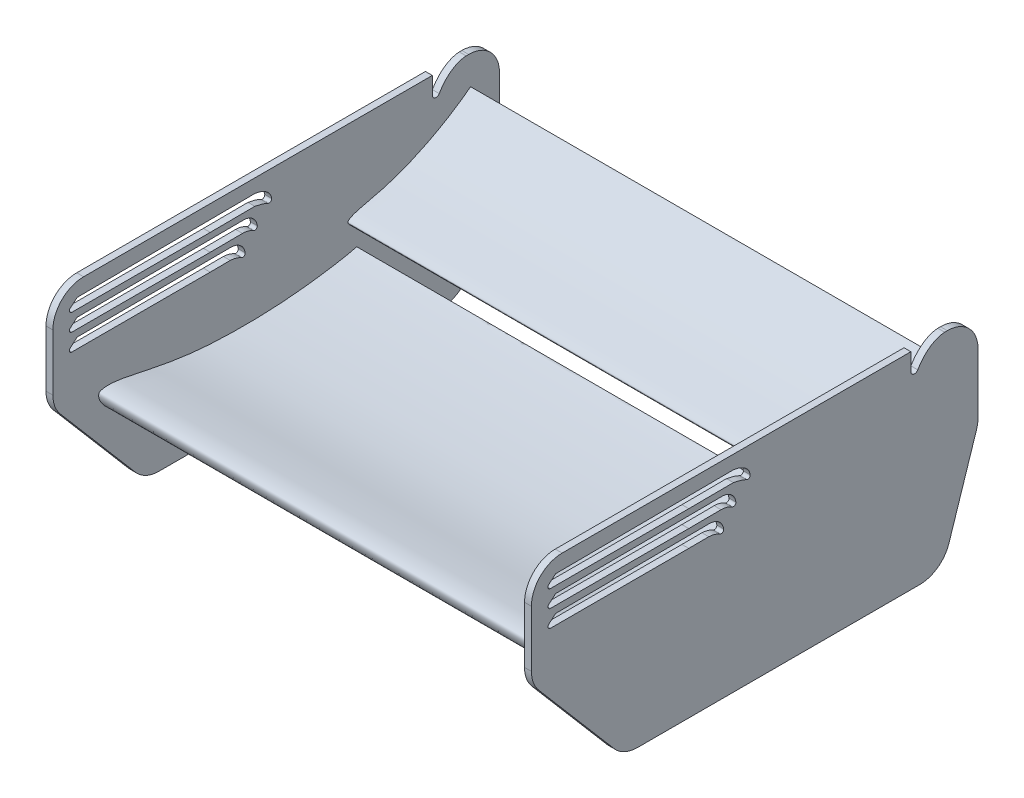
SolidWorks part; units mm, degrees
ref_plane "Front Plane" through (0, 0, 0) normal (0, 0, 1) x (1, 0, 0)
ref_plane "Top Plane" through (0, 0, 0) normal (0, 1, 0) x (1, 0, 0)
ref_plane "Right Plane" through (0, 0, 0) normal (1, 0, 0) x (0, 0, -1)
ref_plane "Soft Top Limit" through (0, 1174.6, 0) normal (0, 1, 0) x (1, 0, 0)
ref_plane "Soft Rear Limit" through (0, 0, -1192.975) normal (0, 0, 1) x (1, 0, 0)
ref_plane "Soft Right Limit" through (-501.65, 0, 0) normal (1, 0, 0) x (0, 0, -1)
ref_plane "Soft Left Limit" through (501.65, 0, 0) normal (1, 0, 0) x (0, 0, -1)
ref_plane "Soft Front Limit" through (0, 0, -165.1) normal (0, 0, 1) x (1, 0, 0)
ref_plane "Slant Limit" through (0, 528.6251, -619.2711) normal (0, -0.6492, 0.7606) x (1, 0, 0)
ref_plane "Bottom" through (0, 476.25, 0) normal (0, 1, 0) x (1, 0, 0)
ref_plane "Midplane" through (0, 0, 0) normal (1, 0, 0) x (0, 0, -1)
curve "Imported Airfoil Curve"
  spline degree 3 poles (0, 2520.0207, 6.126) (0, 2544.889, -1.81) (0, 2521.8965, 7.8839) (0, 2505.3253, 17.7145) (0, 2467.7144, 38.5723) (0, 2424.2142, 62.3813) (0, 2368.0949, 87.8078) (0, 2301.3729, 113.3478) (0, 2223.8362, 140.5377) (0, 2136.6129, 169.2441) (0, 2040.932, 199.097) (0, 1938.2341, 229.6055) (0, 1829.9414, 260.0781) (0, 1717.5266, 289.8586) (0, 1602.4273, 318.1375) (0, 1486.0259, 343.9752) (0, 1369.6902, 366.5754) (0, 1254.3666, 384.7865) (0, 1140.5393, 397.0034) (0, 1028.6357, 403.0127) (0, 919.0585, 402.9406) (0, 812.3986, 397.0375) (0, 709.2785, 385.5985) (0, 610.4299, 369.039) (0, 516.5862, 348.1086) (0, 428.5874, 323.3415) (0, 347.2653, 295.2055) (0, 273.332, 264.2656) (0, 207.4209, 231.0894) (0, 150.0337, 196.3024) (0, 101.596, 160.572) (0, 62.3674, 124.65) (0, 32.4977, 89.3959) (0, 12.0597, 55.6746) (0, 1.683, 26.6201) (0, -0.5567, 6.5526) (0, 0.5894, -3.9947) (0, 1.6947, -9.1451) (0, 2.8711, -12.4915) (0, 3.9449, -14.9776) (0, 4.8993, -16.669) (0, 5.9763, -18.2433) (0, 7.3264, -19.6365) (0, 8.8595, -20.9434) (0, 11.1868, -22.7306) (0, 14.6073, -24.7406) (0, 20.085, -27.4067) (0, 26.8353, -29.9257) (0, 44.6446, -35.1819) (0, 77.8093, -38.8998) (0, 130.2841, -38.2927) (0, 196.3018, -31.4611) (0, 276.2192, -18.4434) (0, 370.8288, 0.8611) (0, 480.7331, 24.811) (0, 605.9792, 50.0099) (0, 745.0759, 74.1542) (0, 895.4497, 95.0846) (0, 1053.6786, 110.004) (0, 1215.6439, 118.3392) (0, 1377.6893, 121.6348) (0, 1537.1174, 120.5125) (0, 1691.5141, 115.2051) (0, 1838.3121, 105.7388) (0, 1975.028, 93.0069) (0, 2099.5942, 78.4581) (0, 2210.5746, 63.1262) (0, 2306.3634, 48.0168) (0, 2387.2069, 33.7158) (0, 2449.0745, 22.0129) (0, 2499.1865, 10.4993) (0, 2520.0207, 6.126) (0, 2544.889, -1.81) (0, 2521.8965, 7.8839) knots -0.016237 -0.007308 -0.001841 0 0.001813 0.006911 0.014576 0.024172 0.035572 0.049013 0.064513 0.081849 0.100772 0.120997 0.142228 0.164173 0.186537 0.209023 0.231367 0.25332 0.274804 0.295858 0.316449 0.336531 0.356033 0.374893 0.39299 0.410197 0.426388 0.441459 0.455334 0.467938 0.479236 0.489204 0.497851 0.505194 0.511308 0.515097 0.516441 0.517273 0.51806 0.518436 0.518797 0.519154 0.519508 0.519887 0.520289 0.52116 0.522116 0.52372 0.525214 0.532575 0.542381 0.554776 0.569931 0.588005 0.609188 0.633329 0.660001 0.688743 0.718873 0.749543 0.780127 0.810209 0.839387 0.867183 0.893104 0.91676 0.937874 0.956199 0.971544 0.983763 0.992692 0.998159 1 1.001813 1.006911 1.014576 periodic
sketch "Airfoils Sketch" plane through (0, 0, 0) normal (1, 0, 0) x (0, 0, -1)
  line L0 (165.1, 1174.6) -> (165.1, 1060.6753) construction
  line L1 (165.1, 1060.6753) -> (663.9798, 476.25) construction
  line L2 (663.9798, 476.25) -> (1192.975, 476.25) construction
  line L3 (1192.975, 476.25) -> (1192.975, 1174.6) construction
  line L4 (1192.975, 1174.6) -> (165.1, 1174.6) construction
  line L5 (509.9361, 1174.6) -> (-509.9361, 1174.6) construction
  line L6 (165.1, 67.0076) -> (165.1, -67.0076) construction
  line L7 (364.7288, 826.8151) -> (873.8134, 230.4351) construction
  line L8 (279.3831, 476.25) -> (-279.3831, 476.25) construction
  line L9 (1192.975, 353.2696) -> (1192.975, -353.2696) construction
  line L10 (364.5896, 868.5327) -> (364.5896, 946) construction
  line L11 (897.9896, 878.5574) -> (897.9896, 1013.4426) construction
  line L12 (897.9896, 946) -> (364.5896, 946) construction
  line L13 (262.9896, 946) -> (1192.975, 946) construction
  line L14 (855.8887, 1048.5614) -> (904.1623, 945.0386) construction
  line L15 (1108.8736, 1167.1505) -> (1157.6222, 1062.6086) construction
  line L16 (1133.2479, 1114.8795) -> (880.0255, 996.8) construction
  line L30 (856.3371, 1047.6) -> (1192.975, 1047.6) construction
  spline S0 degree 3 poles (893.7912, 944.7229) (899.0172, 946.3778) (894.1843, 944.3529) (890.6998, 942.2962) (882.7919, 937.9336) (873.6459, 932.9541) (861.8492, 927.6408) (847.826, 922.3086) (831.5308, 916.6349) (813.2009, 910.6474) (793.0943, 904.4229) (771.5139, 898.0641) (748.7586, 891.7155) (725.138, 885.5141) (700.9544, 879.6292) (676.4985, 874.2577) (652.0578, 869.5659) (627.8318, 865.7954) (603.9228, 863.283) (580.4206, 862.0732) (557.4098, 862.1394) (535.0144, 863.4287) (513.3649, 865.8789) (492.6147, 869.4025) (472.9176, 873.8415) (454.4497, 879.0835) (437.3855, 885.0299) (421.8742, 891.5616) (408.0485, 898.5592) (396.0136, 905.8911) (385.8586, 913.417) (377.6374, 920.9787) (371.3813, 928.3959) (367.1052, 935.4868) (364.9396, 941.5929) (364.4786, 945.8081) (364.7242, 948.0225) (364.9587, 949.1035) (365.2073, 949.8057) (365.434, 950.3273) (365.6352, 950.682) (365.8621, 951.0121) (366.1463, 951.304) (366.4688, 951.5778) (366.9584, 951.952) (367.6776, 952.3725) (368.8291, 952.9298) (370.2479, 953.4556) (373.9902, 954.5511) (380.9564, 955.3164) (391.9757, 955.1645) (405.8359, 953.6991) (422.6123, 950.9282) (442.4709, 946.8302) (465.5393, 941.7496) (491.8288, 936.3995) (521.0273, 931.2645) (552.5956, 926.7991) (585.8161, 923.5923) (619.8244, 921.7664) (653.8518, 920.9989) (687.3317, 921.1602) (719.7569, 922.2028) (750.5884, 924.1223) (779.3042, 926.7322) (805.4694, 929.7293) (828.782, 932.8973) (848.9044, 936.0255) (865.8879, 938.991) (878.8853, 941.4197) (889.4141, 943.8142) (893.7912, 944.7229) (899.0172, 946.3778) (894.1843, 944.3529) knots -0.016237 -0.007308 -0.001841 0 0.001813 0.006911 0.014576 0.024172 0.035572 0.049013 0.064513 0.081849 0.100772 0.120997 0.142228 0.164173 0.186537 0.209023 0.231367 0.25332 0.274804 0.295858 0.316449 0.336531 0.356033 0.374893 0.39299 0.410197 0.426388 0.441459 0.455334 0.467938 0.479236 0.489204 0.497851 0.505194 0.511308 0.515097 0.516441 0.517273 0.51806 0.518436 0.518797 0.519154 0.519508 0.519887 0.520289 0.52116 0.522116 0.52372 0.525214 0.532575 0.542381 0.554776 0.569931 0.588005 0.609188 0.633329 0.660001 0.688743 0.718873 0.749543 0.780127 0.810209 0.839387 0.867183 0.893104 0.91676 0.937874 0.956199 0.971544 0.983763 0.992692 0.998159 1 1.001813 1.006911 1.014576 only from (897.9896, 946) to (897.9896, 946)
  spline S1 degree 3 poles (1131.5375, 1113.3438) (1133.6521, 1115.2864) (1131.806, 1113.2552) (1130.6071, 1111.5075) (1127.8187, 1107.6858) (1124.5791, 1103.2972) (1120.1551, 1098.1634) (1114.6782, 1092.5276) (1108.1983, 1086.2269) (1100.822, 1079.3267) (1092.6546, 1071.9207) (1083.8174, 1064.1247) (1074.4201, 1056.0734) (1064.5795, 1047.9005) (1054.4014, 1039.7532) (1043.9805, 1031.7893) (1033.4164, 1024.1515) (1022.7502, 1016.9986) (1011.956, 1010.5131) (1001.0665, 1004.736) (990.1279, 999.6735) (979.2106, 995.3279) (968.3905, 991.6985) (957.7597, 988.7777) (947.4262, 986.5247) (937.4984, 984.925) (928.0811, 983.9704) (919.2715, 983.6375) (911.1589, 983.8989) (903.8225, 984.7154) (897.3355, 986.0401) (891.7587, 987.81) (887.1468, 989.9462) (883.547, 992.3659) (881.1672, 994.7853) (880.0153, 996.6843) (879.6417, 997.7899) (879.5137, 998.355) (879.4763, 998.7434) (879.4684, 999.0412) (879.4854, 999.2542) (879.52, 999.4611) (879.5903, 999.6626) (879.6829, 999.864) (879.8324, 1000.15) (880.0808, 1000.5088) (880.5041, 1001.0283) (881.0612, 1001.592) (882.5953, 1002.9405) (885.733, 1004.8459) (890.9978, 1007.2132) (897.9021, 1009.5858) (906.4798, 1011.9841) (916.8145, 1014.4348) (928.8905, 1017.1296) (942.5554, 1020.4095) (957.5536, 1024.4354) (973.5286, 1029.3038) (990.0094, 1035.1356) (1006.5584, 1041.7972) (1022.8822, 1048.9655) (1038.7405, 1056.4536) (1053.903, 1064.1266) (1068.1148, 1071.863) (1081.1694, 1079.4589) (1092.9274, 1086.674) (1103.2934, 1093.3387) (1112.1536, 1099.2783) (1119.5597, 1104.4457) (1125.1924, 1108.476) (1129.6607, 1111.9435) (1131.5375, 1113.3438) (1133.6521, 1115.2864) (1131.806, 1113.2552) knots -0.016237 -0.007308 -0.001841 0 0.001813 0.006911 0.014576 0.024172 0.035572 0.049013 0.064513 0.081849 0.100772 0.120997 0.142228 0.164173 0.186537 0.209023 0.231367 0.25332 0.274804 0.295858 0.316449 0.336531 0.356033 0.374893 0.39299 0.410197 0.426388 0.441459 0.455334 0.467938 0.479236 0.489204 0.497851 0.505194 0.511308 0.515097 0.516441 0.517273 0.51806 0.518436 0.518797 0.519154 0.519508 0.519887 0.520289 0.52116 0.522116 0.52372 0.525214 0.532575 0.542381 0.554776 0.569931 0.588005 0.609188 0.633329 0.660001 0.688743 0.718873 0.749543 0.780127 0.810209 0.839387 0.867183 0.893104 0.91676 0.937874 0.956199 0.971544 0.983763 0.992692 0.998159 1 1.001813 1.006911 1.014576 only from (1133.2479, 1114.8795) to (1133.2479, 1114.8795)
  dimension "D1" = 533.4
  dimension "D2" = 228.6
  dimension "D3" = 0
  dimension "D5" = 279.4
  dimension "D6" = 59.7205
extrude "Extruded Airfoils" add sketch "Airfoils Sketch" along normal offset from surface (487.45 mm away) 14.2 up to plane "Soft Left Limit"
sketch "Endplate Sketch" plane through (501.65, 0, 0) normal (1, 0, 0) x (0, 0, -1)
  line L6 (333.4477, 1174.6) -> (1129.475, 1174.6)
  line L7 (1192.975, 1174.6) -> (165.1, 1174.6) construction
  line L8 (1192.975, 1111.1) -> (1192.975, 986.6717)
  line L9 (1192.975, 476.25) -> (1192.975, 1174.6) construction
  line L11 (1189.8464, 966.9854) -> (1132.8969, 792.34)
  line L12 (1072.5255, 748.5263) -> (489.1772, 748.5263)
  line L19 (440.8805, 770.7991) -> (285.151, 953.2323)
  line L26 (269.9477, 994.4595) -> (269.9477, 1111.1)
  line L28 (165.1, 1060.6753) -> (663.9798, 476.25) construction
  arc A12 (1129.475, 1174.6) -> (1192.975, 1111.1) centre (1129.475, 1111.1) cw
  arc A13 (1192.975, 986.6717) -> (1189.8464, 966.9854) centre (1129.475, 986.6717) cw
  arc A14 (1132.8969, 792.34) -> (1072.5255, 748.5263) centre (1072.5255, 812.0263) cw
  arc A15 (489.1772, 748.5263) -> (440.8805, 770.7991) centre (489.1772, 812.0263) cw
  arc A16 (285.151, 953.2323) -> (269.9477, 994.4595) centre (333.4477, 994.4595) cw
  arc A17 (333.4477, 1174.6) -> (269.9477, 1111.1) centre (333.4477, 1111.1) ccw
  point P16 (1192.975, 1174.6)
  point P19 (1192.975, 976.5799)
  point P29 (269.9477, 1174.6)
  dimension "D1" = 63.5
extrude "Extruded Endplate" add sketch "Endplate Sketch" against normal up to surface (14.2 mm away)
mirror "Mirror" about plane through (0, 0, 0) normal (1, 0, 0) of bodies 106
sketch "Sketch1" plane through (501.65, 0, 0) normal (1, 0, 0) x (0, 0, -1)
  line L0 (320.0194, 1134.8548) -> (687.3034, 1134.8548) construction
  line L1 (320.0174, 1144.2924) -> (687.3014, 1146.6068)
  line L2 (595.2277, 1123.1662) -> (687.3014, 1123.7463)
  line L3 (320.0194, 1099.2948) -> (661.9034, 1099.2948) construction
  line L4 (320.0184, 1108.7317) -> (661.9024, 1110.886)
  line L5 (595.1964, 1087.6053) -> (661.9024, 1088.0256)
  line L6 (320.0194, 1063.7348) -> (636.5034, 1063.7348) construction
  line L7 (320.0194, 1073.171) -> (636.5034, 1075.1653)
  line L8 (595.1652, 1052.0444) -> (636.5034, 1052.3048)
  line L9 (320.0174, 1144.2924) -> (305.83, 1132.0987)
  line L10 (309.1412, 1123.1662) -> (595.2277, 1123.1662)
  line L11 (320.0184, 1108.7317) -> (305.8308, 1096.5378)
  line L12 (309.1419, 1087.6053) -> (595.1964, 1087.6053)
  line L13 (320.0194, 1073.171) -> (305.8315, 1060.9769)
  line L14 (309.1427, 1052.0444) -> (595.1652, 1052.0444)
  line L15 (1054.2535, 1174.6) -> (1054.2535, 1138.8789)
  line L16 (1192.975, 1174.6) -> (165.1, 1174.6) construction
  line L18 (1054.2535, 1174.6) -> (1124.125, 1174.6)
  arc A0 (722.057, 1120.5575) -> (714.6998, 1115.3242) centre (717.0281, 1119.8393) cw
  arc A1 (692.4468, 1086.5483) -> (684.7364, 1081.4727) centre (687.4248, 1085.783) cw
  arc A2 (667.3267, 1050.8532) -> (659.819, 1045.5764) centre (662.3191, 1049.9986) cw
  arc A3 (305.8315, 1060.9769) -> (309.1427, 1052.0444) centre (309.1427, 1057.1244) ccw
  arc A4 (305.8308, 1096.5378) -> (309.1419, 1087.6053) centre (309.1419, 1092.6853) ccw
  arc A5 (305.83, 1132.0987) -> (309.1412, 1123.1662) centre (309.1412, 1128.2462) ccw
  arc A6 (1054.2535, 1138.8789) -> (1068.4516, 1135.0329) centre (1061.8735, 1138.8789) ccw
  spline S0 degree 3 poles (687.3014, 1146.6068) (701.9692, 1144.7204) (719.6757, 1137.2305) (722.057, 1120.5575) knots 0 0 0 0 0.846942 0.846942 0.846942 0.846942
  spline S1 degree 3 poles (661.9024, 1110.886) (678.8358, 1111.5075) (690.2297, 1101.0963) (692.4468, 1086.5483) knots 0 0 0 0 0.809071 0.809071 0.809071 0.809071
  spline S2 degree 3 poles (636.5034, 1075.1653) (653.1344, 1075.4271) (664.833, 1065.4654) (667.3267, 1050.8532) knots 0 0 0 0 0.816938 0.816938 0.816938 0.816938
  spline S3 degree 3 poles (687.3014, 1123.7463) (699.2222, 1121.1593) (705.6168, 1120.008) (714.6998, 1115.3242) knots 0 0 0 0 0.77437 0.77437 0.77437 0.77437
  spline S4 degree 3 poles (661.9024, 1088.0256) (669.8975, 1087.9925) (677.9885, 1085.6814) (684.7364, 1081.4727) knots 0 0 0 0 0.706874 0.706874 0.706874 0.706874
  spline S5 degree 3 poles (636.5034, 1052.3048) (644.6814, 1051.9373) (652.7486, 1049.5737) (659.819, 1045.5764) knots 0 0 0 0 0.717847 0.717847 0.717847 0.717847
  spline S6 degree 3 poles (1068.4516, 1135.0329) (1080.1011, 1154.9581) (1099.2172, 1172.7626) (1124.125, 1174.6) knots 0.266304 0.266304 0.266304 0.266304 1 1 1 1
  point P2 (502.8962, 1160.1)
  point P3 (503.6614, 1134.8548)
  point P7 (502.8962, 1117.6567)
  point P9 (490.9614, 1099.2948)
  point P15 (477.7138, 1080.6506)
  point P17 (478.2614, 1063.7348)
  point P22 (465.1954, 1063.7348)
  dimension "D9" = 5.08
  dimension "D10" = 5.08
  dimension "D11" = 5.08
  dimension "D12" = 5.08
  dimension "D13" = 5.08
  dimension "D14" = 5.08
  dimension "D15" = 7.62
  dimension "D1" = 367.284
  dimension "D2" = 341.884
  dimension "D3" = 316.484
  dimension "D4" = 12.7
  dimension "D5" = 12.7
  dimension "D6" = 22.86
  dimension "D7" = 22.86
  dimension "D8" = 22.86
extrude "Cut-Extrude1" cut sketch "Sketch1" against normal through all both and the other way through all
